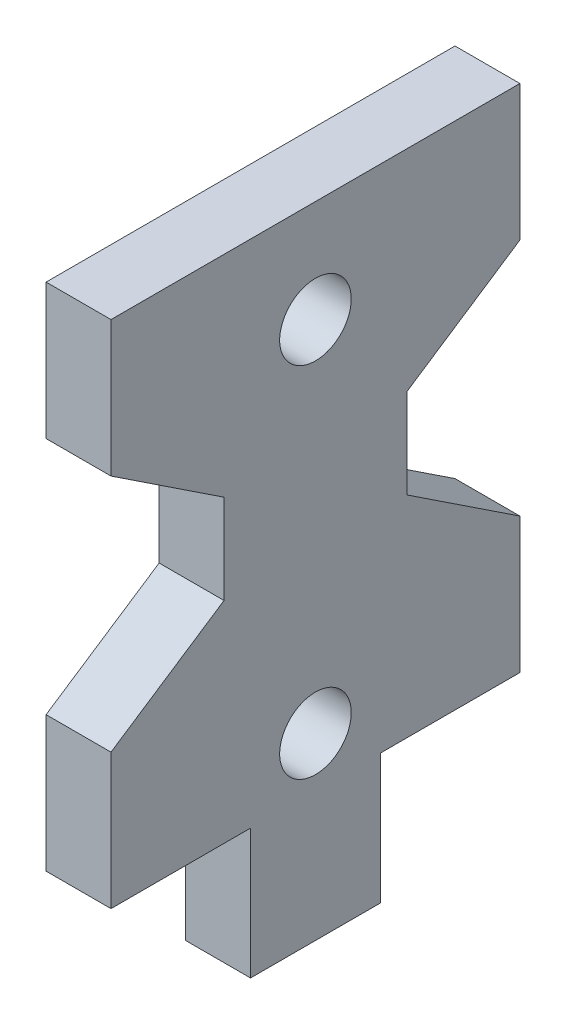
SolidWorks part; units mm, degrees
ref_plane "Front Plane" through (0, 0, 0) normal (0, 0, 1) x (1, 0, 0)
ref_plane "Top Plane" through (0, 0, 0) normal (0, 1, 0) x (1, 0, 0)
ref_plane "Right Plane" through (0, 0, 0) normal (1, 0, 0) x (0, 0, -1)
sketch "Sketch1" plane through (0, 0, 0) normal (1, 0, 0) x (0, 0, -1)
  line L0 (10, 24.952) -> (10, 0) construction
  line L1 (0, 0) -> (6.825, 0)
  line L2 (0, 0) -> (0, 6.6296)
  line L3 (0, 24.952) -> (20, 24.952)
  line L4 (20, 0) -> (20, 6.6296)
  line L5 (0, 18.3224) -> (5.5285, 14.6636)
  line L6 (6.825, -6.35) -> (13.175, -6.35)
  line L7 (6.825, -6.35) -> (6.825, 0)
  line L9 (13.175, -6.35) -> (13.175, 0)
  line L10 (6.825, -6.35) -> (13.175, 0) construction
  line L11 (6.825, 0) -> (13.175, -6.35) construction
  line L12 (5.5285, 14.6636) -> (5.5285, 10.2884)
  line L13 (5.5285, 10.2884) -> (0, 6.6296)
  line L14 (0, 18.3224) -> (0, 24.952)
  line L15 (14.4715, 10.2884) -> (20, 6.6296)
  line L16 (14.4715, 14.6636) -> (14.4715, 10.2884)
  line L17 (20, 18.3224) -> (14.4715, 14.6636)
  line L18 (20, 18.3224) -> (20, 24.952)
  line L19 (13.175, 0) -> (20, 0)
  circle A0 centre (10, 19.952) radius 1.75
  circle A1 centre (10, 2.426) radius 1.75
  point P7 (10, -3.175)
  dimension "D5" = 5
  dimension "D6" = 17.526
  dimension "D1" = 20
  dimension "D2" = 24.952
  dimension "D3" = 6.35
  dimension "D4" = 6.35
extrude "Boss-Extrude1" add sketch "Sketch1" along normal blind 3.175
